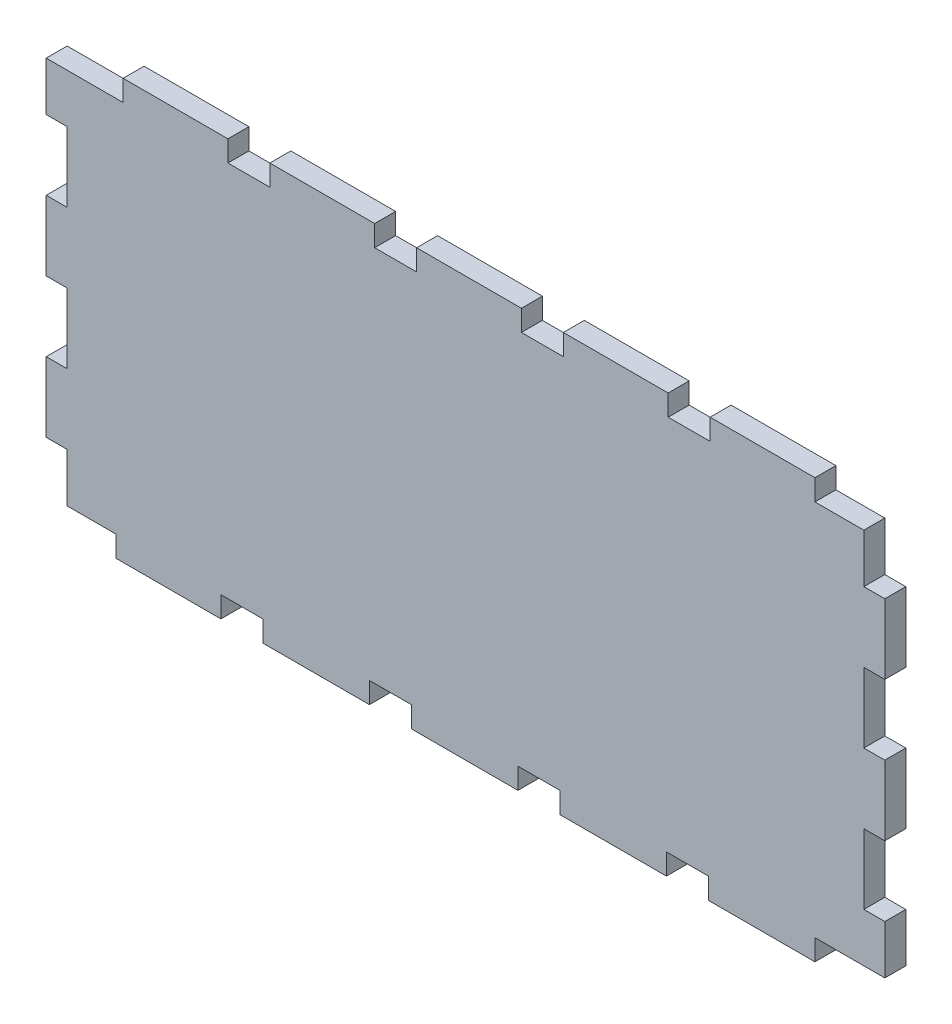
SolidWorks part; units mm, degrees
material "Beech"
ref_plane "Front Plane" through (0, 0, 0) normal (0, 0, 1) x (1, 0, 0)
ref_plane "Top Plane" through (0, 0, 0) normal (0, 1, 0) x (1, 0, 0)
ref_plane "Right Plane" through (0, 0, 0) normal (1, 0, 0) x (0, 0, -1)
sketch "Sketch1" plane through (0, 0, 0) normal (0, 0, 1) x (1, 0, 0)
  line L0 (120, 10) -> (117, 10)
  line L1 (0, 0) -> (120, 0)
  line L2 (0, 0) -> (0, 60)
  line L3 (0, 60) -> (120, 60)
  line L4 (120, 0) -> (120, 60)
  line L5 (117, 10) -> (117, 20)
  line L6 (117, 20) -> (120, 20)
  line L7 (117, 40) -> (120, 40)
  line L8 (117, 30) -> (117, 40)
  line L9 (120, 30) -> (117, 30)
  line L10 (117, 60) -> (120, 60)
  line L11 (117, 50) -> (117, 60)
  line L12 (120, 50) -> (117, 50)
  line L13 (3, 3) -> (10, 3)
  line L14 (10, 3) -> (10, 0)
  line L15 (25, 0) -> (25, 3)
  line L16 (25, 3) -> (31, 3)
  line L17 (31, 3) -> (31, 0)
  line L18 (46.25, 0) -> (46.25, 3)
  line L19 (52.25, 3) -> (52.25, 0)
  line L20 (46.25, 3) -> (52.25, 3)
  line L21 (67.5, 0) -> (67.5, 3)
  line L22 (73.5, 3) -> (73.5, 0)
  line L23 (67.5, 3) -> (73.5, 3)
  line L24 (88.75, 0) -> (88.75, 3)
  line L25 (94.75, 3) -> (94.75, 0)
  line L26 (88.75, 3) -> (94.75, 3)
  line L27 (110, 0) -> (110, 3)
  line L28 (116, 3) -> (116, 0)
  line L29 (110, 3) -> (116, 3)
  line L30 (110, 60) -> (110, 57)
  line L31 (110, 57) -> (117, 57)
  line L32 (95, 60) -> (95, 57)
  line L33 (95, 57) -> (89, 57)
  line L34 (0, 50) -> (3, 50)
  line L35 (3, 50) -> (3, 40)
  line L36 (3, 40) -> (0, 40)
  line L37 (3, 20) -> (0, 20)
  line L38 (3, 30) -> (3, 20)
  line L39 (0, 30) -> (3, 30)
  line L40 (3, 0) -> (0, 0)
  line L41 (3, 10) -> (3, 0)
  line L42 (0, 10) -> (3, 10)
  line L43 (89, 57) -> (89, 60)
  line L44 (74, 60) -> (74, 57)
  line L45 (74, 57) -> (68, 57)
  line L46 (68, 57) -> (68, 60)
  line L47 (53, 60) -> (53, 57)
  line L48 (53, 57) -> (47, 57)
  line L49 (47, 57) -> (47, 60)
  line L50 (32, 60) -> (32, 57)
  line L51 (32, 57) -> (26, 57)
  line L52 (26, 57) -> (26, 60)
  line L53 (11, 60) -> (11, 57)
  line L54 (11, 57) -> (5, 57)
  line L55 (5, 57) -> (5, 60)
  line L56 (5, 57) -> (0, 57)
  line L57 (116, 3) -> (120, 3)
  point P45 (110, 58.5)
  dimension "D1" = 120
  dimension "D2" = 60
  dimension "D3" = 3
  dimension "D4" = 10
  dimension "D5" = 10
  dimension "D7" = 10
  dimension "D8" = 3
  dimension "D9" = 15
  dimension "D11" = 10
  dimension "D12" = 10
  dimension "D13" = 3
  dimension "D10" = 6
  dimension "D15" = 3
  dimension "D16" = 3
  dimension "D17" = 10
  dimension "D18" = 6
  dimension "D19" = 15
  dimension "D20" = 3
  dimension "D14" = 3
  dimension "D6" = 3
extrude "Boss-Extrude1" add sketch "Sketch1" along normal blind 3 contours L54 L55 L3 L2 L34 L35 L36 L39 L38 L37 L42 L41 L13 L14 L1 L15 L16 L17 L18 L20 L19 L21 L23 L22 L24 L26 L25 L27 L29 L28 L4 L0 L5 L6 L9 L8 L7 L12 L11 L31 L30
